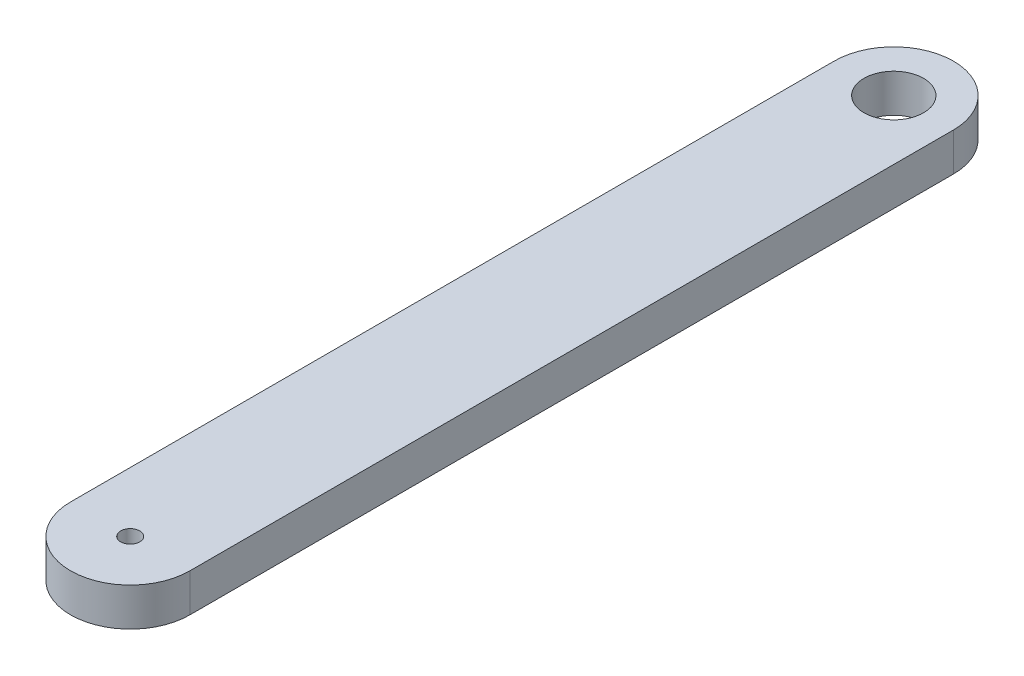
SolidWorks part; units mm, degrees
ref_plane "Front Plane" through (0, 0, 0) normal (0, 0, 1) x (1, 0, 0)
ref_plane "Top Plane" through (0, 0, 0) normal (0, 1, 0) x (1, 0, 0)
ref_plane "Right Plane" through (0, 0, 0) normal (1, 0, 0) x (0, 0, -1)
sketch "Sketch1" plane through (0, 0, 0) normal (0, 1, 0) x (1, 0, 0)
  line L0 (0, 0) -> (0, 160) construction
  line L1 (0, 80) -> (-25.4869, 80) construction
  line L2 (12.5, 160) -> (12.5, 0)
  line L3 (-12.5, 160) -> (-12.5, 0)
  circle A0 centre (0, 0) radius 2
  circle A1 centre (0, 0) radius 12.5
  circle A2 centre (0, 160) radius 12.5
  circle A3 centre (0, 160) radius 6.25
  dimension "D2" = 12.5
  dimension "D3" = 4
  dimension "D4" = 25
  dimension "D1" = 160
  dimension "D5" = 25
extrude "Boss-Extrude1" add sketch "Sketch1" along normal blind 8 contours A2 L3 A1 L2 | A2 A3 | A1
